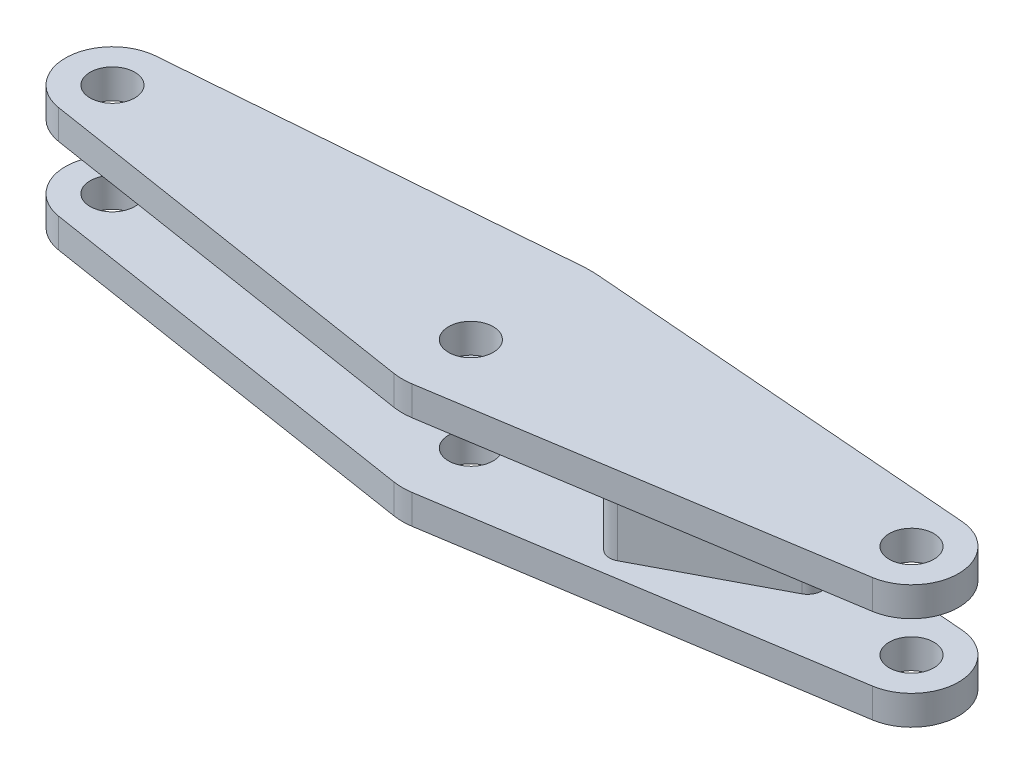
SolidWorks part; units mm, degrees
ref_plane "Front Plane" through (0, 0, 0) normal (0, 0, 1) x (1, 0, 0)
ref_plane "Top Plane" through (0, 0, 0) normal (0, 1, 0) x (1, 0, 0)
ref_plane "Right Plane" through (0, 0, 0) normal (1, 0, 0) x (0, 0, -1)
sketch "Sketch1" plane through (0, 0, 0) normal (0, 1, 0) x (1, 0, 0)
  line L0 (-17, 0) -> (17, 0) construction
  line L1 (0, 3.35) -> (0, -4.6963) construction
  line L2 (-0.394, 3.3189) -> (-17.1576, 1.9938)
  line L3 (-0.3881, -4.6353) -> (-17.3105, -1.9757)
  line L4 (0.394, 3.3189) -> (17.1576, 1.9938)
  line L5 (0.3881, -4.6353) -> (17.3105, -1.9757)
  circle A0 centre (-17, 0) radius 0.95
  arc A1 (-17.1576, 1.9938) -> (-17.3105, -1.9757) centre (-17, 0) ccw
  circle A2 centre (17, 0) radius 0.95
  arc A3 (17.3105, -1.9757) -> (17.1576, 1.9938) centre (17, 0) ccw
  arc A4 (0.394, 3.3189) -> (-0.394, 3.3189) centre (0, -1.6656) ccw
  arc A5 (0.3881, -4.6353) -> (-0.3881, -4.6353) centre (0, -2.1656) cw
  circle A6 centre (0, -1.75) radius 0.95
  point P4 (0, 0)
  point P7 (0, 0)
  dimension "D4" = 4
  dimension "D5" = 1.9
  dimension "D6" = 4
  dimension "D7" = 1.9
  dimension "D8" = 5
  dimension "D9" = 2.5
  dimension "D10" = 1.9
  dimension "D2" = 8
  dimension "D1" = 34
  dimension "D3" = 3.35
  dimension "D11" = 1.75
extrude "Boss-Extrude1" add sketch "Sketch1" along normal mid plane 5.25
sketch "Sketch3" plane through (0, 0, 0) normal (0, 0, 1) x (1, 0, 0)
  line L0 (19, -2.625) -> (19, 2.625) construction
  line L1 (-19, 1.375) -> (19, 1.375)
  line L2 (-19, 1.375) -> (-19, -1.375)
  line L3 (-19, -1.375) -> (19, -1.375)
  line L4 (19, 1.375) -> (19, -1.375)
  line L5 (-19, 1.375) -> (19, -1.375) construction
  line L6 (-19, -1.375) -> (19, 1.375) construction
  line L7 (0.3881, 2.625) -> (17.3105, 2.625) construction
  point P0 (0, 0)
  dimension "D1" = 1.25
extrude "Cut-Extrude1" cut sketch "Sketch3" against normal through all both and the other way through all
sketch "Sketch4" plane through (0, 0, 0) normal (0, 1, 0) x (1, 0, 0)
  line L0 (0, 0) -> (13.4196, 0) construction
  line L1 (1.7419, 0.45) -> (12.1332, 0.45) construction
  line L2 (12.1332, 0.45) -> (7, -2.25) construction
  line L3 (12.4125, -0.081) -> (7.2793, -2.781)
  line L4 (11.8539, 0.981) -> (6.7207, -1.719)
  arc A0 (12.4125, -0.081) -> (11.8539, 0.981) centre (12.1332, 0.45) ccw
  arc A1 (6.7207, -1.719) -> (7.2793, -2.781) centre (7, -2.25) ccw
  point P5 (9.5666, -0.9)
  dimension "D2" = 0.6
  dimension "D1" = 5.8
  dimension "D3" = 0.45
  dimension "D4" = 2.25
  dimension "D5" = 7
extrude "Boss-Extrude2" add sketch "Sketch4" along normal up to next (2.625 mm away) and the other way up to next (1.375 mm away)
